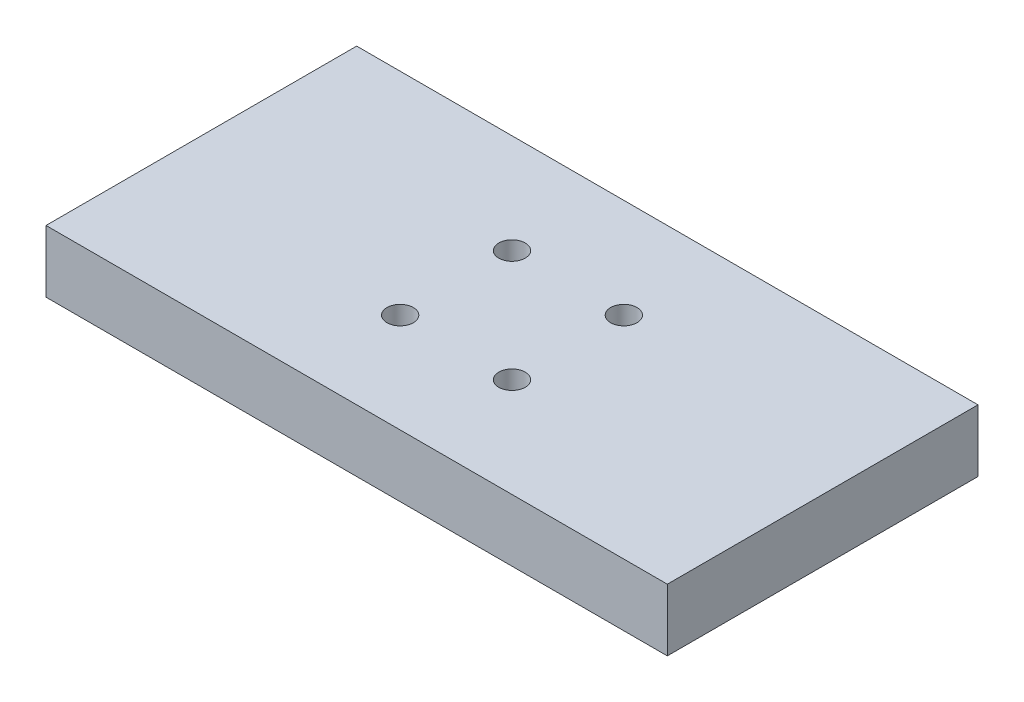
SolidWorks part; units mm, degrees
ref_plane "Alzado" through (0, 0, 0) normal (0, 0, 1) x (1, 0, 0)
ref_plane "Planta" through (0, 0, 0) normal (0, 1, 0) x (1, 0, 0)
ref_plane "Vista lateral" through (0, 0, 0) normal (1, 0, 0) x (0, 0, -1)
sketch "Croquis1" plane through (0, 0, 0) normal (0, 1, 0) x (1, 0, 0)
  line L1 (-100, 50) -> (100, 50)
  line L2 (-100, 50) -> (-100, -50)
  line L3 (-100, -50) -> (100, -50)
  line L4 (100, 50) -> (100, -50)
  line L5 (-100, 50) -> (100, -50) construction
  line L6 (-100, -50) -> (100, 50) construction
  point P0 (0, 0)
  dimension "D1" = 100
  dimension "D2" = 200
extrude "Saliente-Extruir1" add sketch "Croquis1" along normal blind 20
sketch "Croquis2" plane through (0, 0, 0) normal (0, -1, 0) x (1, 0, 0)
  line L1 (-18, 18) -> (18, 18) construction
  line L2 (-18, 18) -> (-18, -18) construction
  line L3 (-18, -18) -> (18, -18) construction
  line L4 (18, 18) -> (18, -18) construction
  line L5 (-18, 18) -> (18, -18) construction
  line L6 (-18, -18) -> (18, 18) construction
  circle A0 centre (-18, 18) radius 7
  circle A1 centre (-18, -18) radius 7
  circle A2 centre (18, 18) radius 7
  circle A3 centre (18, -18) radius 7
  point P0 (0, 0)
  dimension "D3" = 14
  dimension "D4" = 14
  dimension "D5" = 14
  dimension "D6" = 14
  dimension "D1" = 36
  dimension "D2" = 36
extrude "Cortar-Extruir1" cut sketch "Croquis2" against normal blind 9
sketch "Croquis3" plane through (0, 9, 0) normal (0, -1, 0) x (1, 0, 0)
  circle A0 centre (-18, 18) radius 4.25
  circle A1 centre (18, 18) radius 4.25
  circle A2 centre (18, -18) radius 4.25
  circle A3 centre (-18, -18) radius 4.25
  dimension "D1" = 8.5
  dimension "D2" = 8.5
  dimension "D3" = 8.5
  dimension "D4" = 8.5
extrude "Cortar-Extruir2" cut sketch "Croquis3" against normal through all
